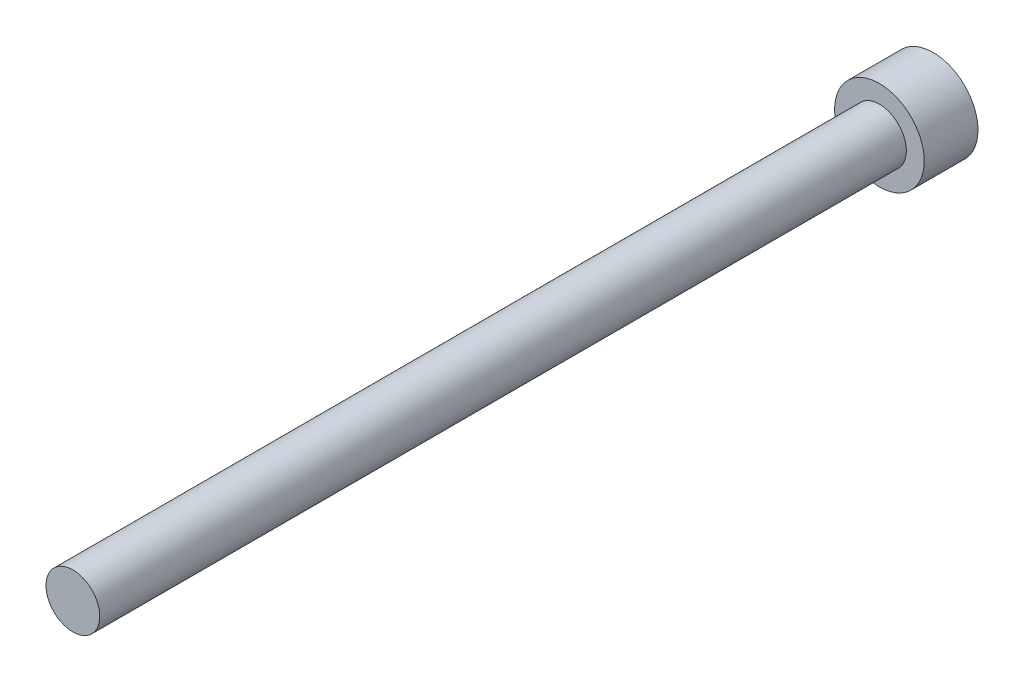
SolidWorks part; units mm, degrees
material "AISI 4340 Steel, normalized"
ref_plane "Front Plane" through (0, 0, 0) normal (0, 0, 1) x (1, 0, 0)
ref_plane "Top Plane" through (0, 0, 0) normal (0, 1, 0) x (1, 0, 0)
ref_plane "Right Plane" through (0, 0, 0) normal (1, 0, 0) x (0, 0, -1)
sketch "Sketch1" plane through (0, 0, 0) normal (0, 0, 1) x (1, 0, 0)
  circle A0 centre (0, 0) radius 5
extrude "Head_Envelope" add sketch "Sketch1" along normal blind 6 from offset 6
sketch "Sketch2" plane through (0, 0, 0) normal (0, 0, 1) x (1, 0, 0)
  circle A0 centre (0, 0) radius 3
extrude "Thread_Major_Envelope" add sketch "Sketch2" along normal blind 90
